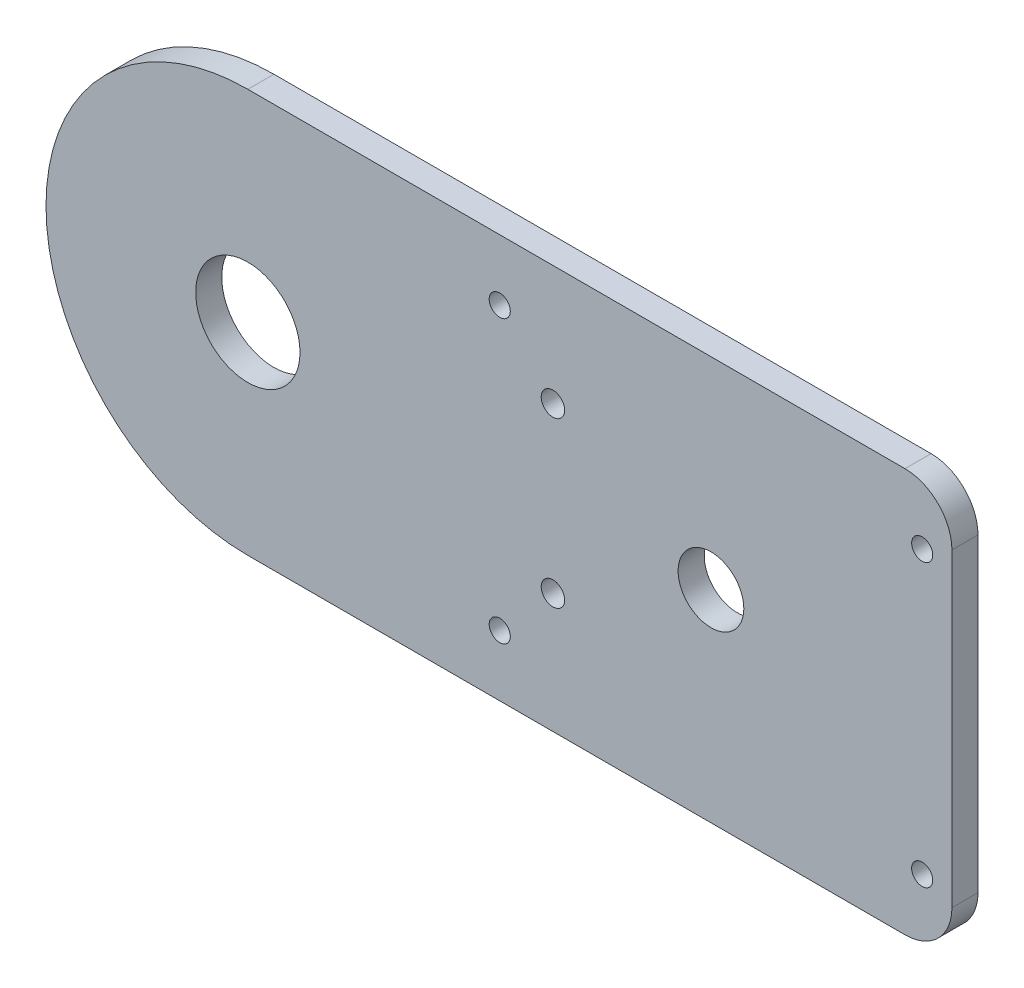
SolidWorks part; units mm, degrees
ref_plane "Front Plane" through (0, 0, 0) normal (0, 0, 1) x (1, 0, 0)
ref_plane "Top Plane" through (0, 0, 0) normal (0, 1, 0) x (1, 0, 0)
ref_plane "Right Plane" through (0, 0, 0) normal (1, 0, 0) x (0, 0, -1)
sketch "Sketch1" plane through (0, 0, 0) normal (0, 0, 1) x (1, 0, 0)
  line L0 (-65, 43) -> (85, 43)
  line L1 (85, 43) -> (85, -43)
  line L2 (85, -43) -> (-65, -43)
  circle A0 centre (-65, 0) radius 11.1125
  arc A1 (-65, 43) -> (-65, -43) centre (-65, 0) ccw
  dimension "D1" = 43
  dimension "D2" = 150
extrude "Boss-Extrude1" add sketch "Sketch1" along normal blind 5.5562
sketch "Sketch2" plane through (0, 0, 5.5562) normal (0, 0, 1) x (1, 0, 0)
  circle A0 centre (33.6664, 0) radius 7
  dimension "D1" = 14
  dimension "D2" = 33.6664
extrude "Cut-Extrude1" cut sketch "Sketch2" against normal blind 5.5562
fillet "Fillet1" radius 10 2 edges at (85, -43, 2.7781) (85, 43, 2.7781)
sketch "Sketch3" plane through (0, 0, 5.5562) normal (0, 0, 1) x (1, 0, 0)
  line L1 (-11.3336, -30) -> (78.6664, -30) construction
  line L2 (-11.3336, -30) -> (-11.3336, 30) construction
  line L3 (-11.3336, 30) -> (78.6664, 30) construction
  line L4 (78.6664, -30) -> (78.6664, 30) construction
  line L5 (-11.3336, -30) -> (78.6664, 30) construction
  line L6 (-11.3336, 30) -> (78.6664, -30) construction
  circle A0 centre (78.6664, 30) radius 2.25
  circle A1 centre (78.6664, -30) radius 2.25
  circle A2 centre (-11.3336, 30) radius 2.25
  circle A3 centre (-11.3336, -30) radius 2.25
  point P0 (33.6664, 0)
  dimension "D1" = 90
  dimension "D2" = 60
extrude "Cut-Extrude2" cut sketch "Sketch3" against normal blind 6.35
sketch "Sketch4" plane through (0, 0, 5.5562) normal (0, 0, 1) x (1, 0, 0)
  line L0 (0, -17.5) -> (0, 17.5) construction
  circle A1 centre (0, 17.5) radius 2.5
  circle A2 centre (0, -17.5) radius 2.5
  point P4 (0, 0)
  dimension "D1" = 5
extrude "Cut-Extrude3" cut sketch "Sketch4" against normal blind 40
